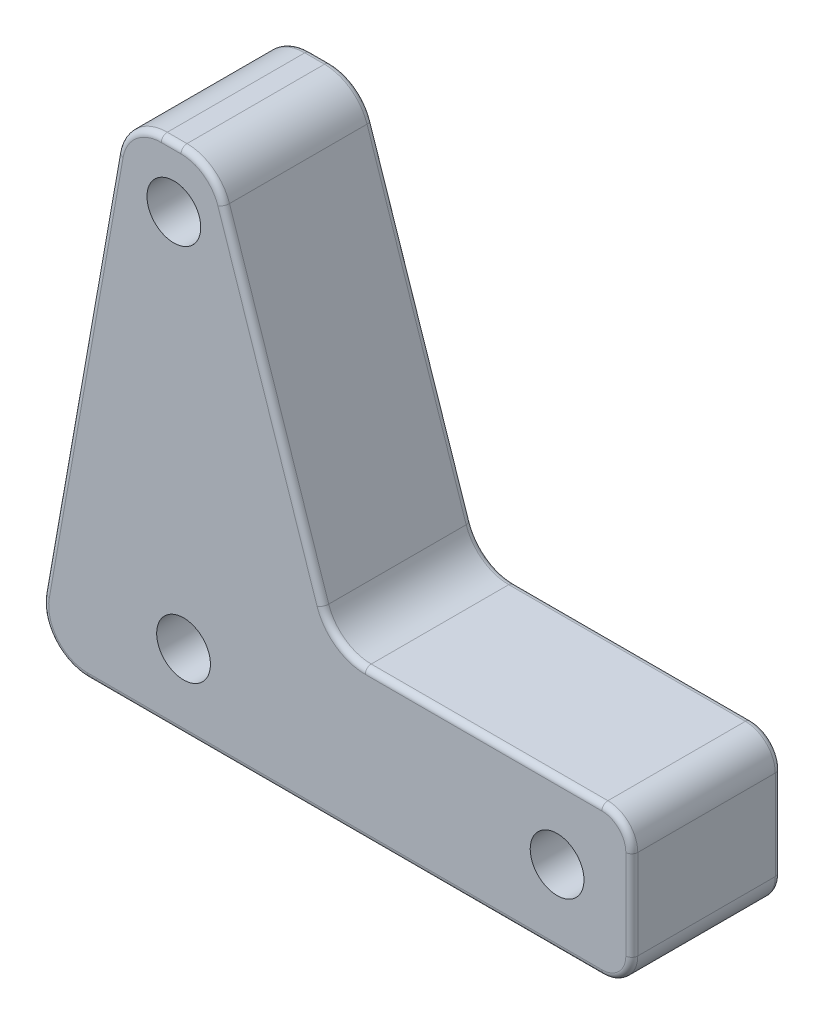
SolidWorks part; units mm, degrees
ref_plane "Front Plane" through (0, 0, 0) normal (0, 0, 1) x (1, 0, 0)
ref_plane "Top Plane" through (0, 0, 0) normal (0, 1, 0) x (1, 0, 0)
ref_plane "Right Plane" through (0, 0, 0) normal (1, 0, 0) x (0, 0, -1)
sketch "Sketch1" plane through (0, 0, 0) normal (0, 0, 1) x (1, 0, 0)
  line L2 (7.6138, 43.18) -> (0, 0)
  line L3 (15.2338, 43.18) -> (25.4, 12.7)
  line L4 (25.4, 12.7) -> (50.8, 12.7)
  line L5 (50.8, 12.7) -> (50.8, 0)
  line L7 (0, 0) -> (50.8, 0)
  line L8 (7.6138, 43.18) -> (15.2338, 43.18)
  circle A0 centre (11.8764, 38.1) radius 2.286
  point P4 (13.4832, 44.45)
  dimension "D5" = 4.572
  dimension "D1" = 50.8
  dimension "D2" = 5.08
  dimension "D3" = 12.7
  dimension "D4" = 25.4
  dimension "D6" = 5.08
  dimension "D7" = 38.1
  dimension "D8" = 80
  dimension "D9" = 7.62
extrude "Boss-Extrude1" add sketch "Sketch1" along normal blind 12.7
fillet "Fillet2" radius 3.81 4 edges at (0, 0, 6.35) (25.4, 12.7, 6.35) (15.2338, 43.18, 6.35) (7.6138, 43.18, 6.35)
sketch "Sketch4" plane through (0, 12.7, 0) normal (0, 1, 0) x (1, 0, 0)
  line L0 (50.8, -12.7) -> (50.8, 0) construction
  line L1 (50.8, -12.7) -> (28.1456, -12.7) construction
  circle A0 centre (44.45, -6.35) radius 2.032
  dimension "D1" = 4.064
  dimension "D2" = 6.35
  dimension "D3" = 6.35
extrude "Cut-Extrude2" [suppressed] cut sketch "Sketch4" against normal through all both and the other way through all
fillet "Fillet3" radius 2.54 2 edges at (50.8, 0, 6.35) (50.8, 12.7, 6.35)
sketch "Sketch5" plane through (0, 0, 0) normal (-0.9848, 0.1736, 0) x (0, 0, 1)
  line L0 (12.7, 0.7885) -> (0, 0.7885) construction
  line L1 (0, 40.6492) -> (0, 4.5406) construction
  circle A0 centre (6.35, 33.8085) radius 2.032
  circle A1 centre (6.35, 8.4085) radius 2.032
  dimension "D1" = 4.064
  dimension "D2" = 33.02
  dimension "D3" = 6.35
  dimension "D4" = 2
extrude "Cut-Extrude3" [suppressed] cut sketch "Sketch5" against normal blind 6.35 and the other way through all
sketch "Sketch6" plane through (0, 0, 0) normal (0, 0, -1) x (-1, 0, 0)
  line L0 (-50.8, 2.54) -> (-50.8, 10.16) construction
  line L1 (-48.26, 12.7) -> (-28.1456, 12.7) construction
  circle A0 centre (-44.45, 6.35) radius 2.286
  circle A1 centre (-12.7, 6.35) radius 2.286
  point P6 (0, 0)
  dimension "D1" = 4.572
  dimension "D2" = 6.35
  dimension "D3" = 6.35
  dimension "D4" = 31.75
extrude "Cut-Extrude4" cut sketch "Sketch6" against normal through all
fillet "Fillet4" radius 0.508 24 edges at (50.0561, 11.9561, 0) (50.8, 6.35, 0) (50.0561, 0.7439, 0) (26.4003, 0, 0) (1.622, 1.361, 0) (3.9236, 22.2516, 0) (20.3169, 27.94, 0) (25.9181, 13.419, 0) (25.9181, 13.419, 12.7) (38.2028, 12.7, 12.7) (50.0561, 11.9561, 12.7) (50.8, 6.35, 12.7) (50.0561, 0.7439, 12.7) (26.4003, 0, 12.7) (1.622, 1.361, 12.7) (3.9236, 22.2516, 12.7) (38.2028, 12.7, 0) (20.3169, 27.94, 12.7) (8.3617, 42.2886, 0) (11.6495, 43.18, 0) (14.7157, 42.461, 0) (8.3617, 42.2886, 12.7) (11.6495, 43.18, 12.7) (14.7157, 42.461, 12.7)
